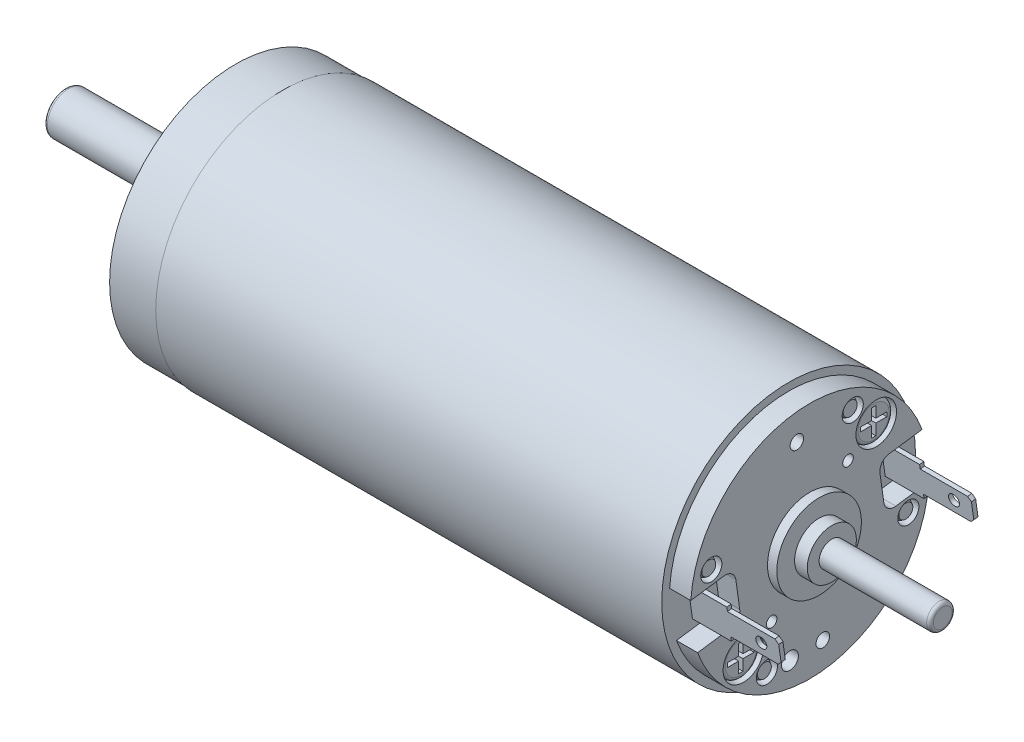
SolidWorks part; units mm, degrees
ref_plane "Front Plane" through (0, 0, 0) normal (0, 0, 1) x (1, 0, 0)
ref_plane "Top Plane" through (0, 0, 0) normal (0, 1, 0) x (1, 0, 0)
ref_plane "Right Plane" through (0, 0, 0) normal (1, 0, 0) x (0, 0, -1)
sketch "Sketch1" plane through (0, 0, 0) normal (0, 0, 1) x (1, 0, 0)
  line L0 (5.7, 15) -> (5.7, 0)
  line L1 (5.7, 0) -> (65.5, 0)
  line L2 (65.5, 0) -> (65.5, 15)
  line L3 (65.5, 15) -> (5.7, 15)
  line L4 (5.7, 0) -> (65.5, 0) construction
revolve "Revolve1" add sketch "Sketch1" angle 360 about L4
sketch "Sketch2" plane through (65.5, 0, 0) normal (1, 0, 0) x (0, 0, -1)
  line L0 (11.9001, -0.2462) -> (11.4049, -0.3158)
  line L1 (11.4049, -0.3158) -> (10.8761, 3.4472)
  line L2 (10.8761, 3.4472) -> (11.3712, 3.5168)
  line L3 (11.3712, 3.5168) -> (11.9001, -0.2462)
extrude "Boss-Extrude1" add sketch "Sketch2" along normal blind 10.6
sketch "Sketch3" plane through (0, 1.5657, -11.1405) normal (0, -0.1392, 0.9903) x (1, 0, 0)
  line L0 (70.1, 1.4) -> (76.1, 1.4)
  line L1 (76.1, 1.4) -> (76.1, 1.9)
  line L2 (76.1, 1.9) -> (70.1, 1.9)
  line L3 (70.1, 1.9) -> (70.1, 1.4)
extrude "Cut-Extrude1" cut sketch "Sketch3" against normal through all
sketch "Sketch4" plane through (0, 1.5657, -11.1405) normal (0, -0.1392, 0.9903) x (1, 0, 0)
  line L0 (70.1, -1.4) -> (70.1, -1.9)
  line L1 (70.1, -1.9) -> (76.1, -1.9)
  line L2 (76.1, -1.9) -> (76.1, -1.4)
  line L3 (76.1, -1.4) -> (70.1, -1.4)
extrude "Cut-Extrude2" cut sketch "Sketch4" against normal through all
sketch "Sketch5" plane through (65.5, 0, 0) normal (1, 0, 0) x (0, 0, -1)
  line L0 (-11.9001, 0.2462) -> (-11.4049, 0.3158)
  line L1 (-11.4049, 0.3158) -> (-10.8761, -3.4472)
  line L2 (-10.8761, -3.4472) -> (-11.3712, -3.5168)
  line L3 (-11.3712, -3.5168) -> (-11.9001, 0.2462)
extrude "Boss-Extrude2" add sketch "Sketch5" along normal blind 10.6
sketch "Sketch6" plane through (0, -1.5657, 11.1405) normal (0, 0.1392, -0.9903) x (-1, 0, 0)
  line L0 (-76.1, -1.9) -> (-70.1, -1.9)
  line L1 (-70.1, -1.9) -> (-70.1, -1.4)
  line L2 (-70.1, -1.4) -> (-76.1, -1.4)
  line L3 (-76.1, -1.4) -> (-76.1, -1.9)
extrude "Cut-Extrude3" cut sketch "Sketch6" against normal through all
sketch "Sketch7" plane through (0, -1.5657, 11.1405) normal (0, 0.1392, -0.9903) x (-1, 0, 0)
  line L0 (-76.1, 1.9) -> (-76.1, 1.4)
  line L1 (-76.1, 1.4) -> (-70.1, 1.4)
  line L2 (-70.1, 1.4) -> (-70.1, 1.9)
  line L3 (-70.1, 1.9) -> (-76.1, 1.9)
extrude "Cut-Extrude4" cut sketch "Sketch7" against normal through all
sketch "Sketch8" plane through (5.7, 0, 0) normal (-1, 0, 0) x (0, 0, 1)
  circle A0 centre (0, 0) radius 14.9
extrude "Boss-Extrude3" add sketch "Sketch8" along normal blind 5.55
sketch "Sketch9" plane through (0.15, 0, 0) normal (-1, 0, 0) x (0, 0, 1)
  circle A0 centre (0, 0) radius 13.5
extrude "Boss-Extrude4" add sketch "Sketch9" along normal blind 0.15
sketch "Sketch10" plane through (0, 0, 0) normal (-1, 0, 0) x (0, 0, 1)
  circle A0 centre (0, 0) radius 8
extrude "Boss-Extrude5" add sketch "Sketch10" along normal blind 1.1
sketch "Sketch11" plane through (-1.1, 0, 0) normal (-1, 0, 0) x (0, 0, 1)
  circle A0 centre (0, 0) radius 4.5
extrude "Boss-Extrude6" add sketch "Sketch11" along normal blind 2.15
sketch "Sketch12" plane through (-3.25, 0, 0) normal (-1, 0, 0) x (0, 0, 1)
  circle A0 centre (0, 0) radius 2.5
  dimension "D1" = 5
extrude "Boss-Extrude7" add sketch "Sketch12" along normal blind 16.75
sketch "Sketch13" plane through (65.5, 0, 0) normal (1, 0, 0) x (0, 0, -1)
  line L0 (-8.9199, 1.6749) -> (-14.0679, 0.9514)
  line L1 (13.2607, 4.7922) -> (8.1127, 4.0687)
  line L2 (8.1127, 4.0687) -> (8.9199, -1.6749)
  line L3 (8.9199, -1.6749) -> (14.0679, -0.9514)
  line L4 (-13.2607, -4.7922) -> (-8.1127, -4.0687)
  line L5 (-8.1127, -4.0687) -> (-8.9199, 1.6749)
  arc A0 (-14.0679, 0.9514) -> (13.2607, 4.7922) centre (0, 0) cw
  arc A1 (14.0679, -0.9514) -> (-13.2607, -4.7922) centre (0, 0) cw
extrude "Boss-Extrude8" add sketch "Sketch13" along normal blind 2.5
sketch "Sketch14" plane through (68, 0, 0) normal (1, 0, 0) x (0, 0, -1)
  circle A0 centre (0, 0) radius 5
extrude "Boss-Extrude9" add sketch "Sketch14" along normal blind 1.1
sketch "Sketch15" plane through (69.1, 0, 0) normal (1, 0, 0) x (0, 0, -1)
  circle A0 centre (0, 0) radius 2.9
extrude "Boss-Extrude10" add sketch "Sketch15" along normal blind 1.5
sketch "Sketch16" plane through (70.6, 0, 0) normal (1, 0, 0) x (0, 0, -1)
  circle A0 centre (0, 0) radius 1.5
extrude "Boss-Extrude11" add sketch "Sketch16" along normal blind 13.1
hole_wizard "Ø2.5 (2.5) Diameter Hole1" positions "Sketch18" profile "Sketch17" hole size "Ø2.5" standard "Ansi Metric"
sketch "Sketch18" plane through (68, 0, 0) normal (1, 0, 0) x (0, 0, -1)
  point P0 (11.6435, -2.9031)
sketch "Sketch17" plane through (68, -2.9031, -11.6435) normal (0, 1, 0) x (0, 0, -1)
  line L0 (0, 0) -> (0, 1.3)
  line L1 (0, 1.3) -> (1.25, 1.3)
  line L2 (1.25, 1.3) -> (1.25, 0)
  line L5 (1.25, 0) -> (0, 0)
  line L10 (0, 1.3) -> (-1.25, 1.3) construction
  line L11 (0, -6.35) -> (0, 107.95) construction
  dimension "Hole Dia." = 2.5
  dimension "Hole Depth" = 1.3
  dimension "Drill Angle" = 180
sketch "Sketch19" plane through (66.7, 0, 0) normal (1, 0, 0) x (0, 0, -1)
  circle A0 centre (11.6435, -2.9031) radius 1
extrude "Boss-Extrude12" add sketch "Sketch19" along normal blind 1
hole_wizard "Ø2.5 (2.5) Diameter Hole2" positions "Sketch21" profile "Sketch20" hole size "Ø2.5" standard "Ansi Metric"
sketch "Sketch21" plane through (68, 0, 0) normal (1, 0, 0) x (0, 0, -1)
  point P0 (5.0714, 10.8757)
sketch "Sketch20" plane through (68, 10.8757, -5.0714) normal (0, 1, 0) x (0, 0, -1)
  line L0 (0, 0) -> (0, 1.3)
  line L1 (0, 1.3) -> (1.25, 1.3)
  line L2 (1.25, 1.3) -> (1.25, 0)
  line L5 (1.25, 0) -> (0, 0)
  line L10 (0, 1.3) -> (-1.25, 1.3) construction
  line L11 (0, -6.35) -> (0, 107.95) construction
  dimension "Hole Dia." = 2.5
  dimension "Hole Depth" = 1.3
  dimension "Drill Angle" = 180
sketch "Sketch22" plane through (66.7, 0, 0) normal (1, 0, 0) x (0, 0, -1)
  circle A0 centre (5.0714, 10.8757) radius 1
extrude "Boss-Extrude13" add sketch "Sketch22" along normal blind 1
hole_wizard "Ø2.5 (2.5) Diameter Hole3" positions "Sketch24" profile "Sketch23" hole size "Ø2.5" standard "Ansi Metric"
sketch "Sketch24" plane through (68, 0, 0) normal (1, 0, 0) x (0, 0, -1)
  point P0 (-11.6435, 2.9031)
sketch "Sketch23" plane through (68, 2.9031, 11.6435) normal (0, 1, 0) x (0, 0, -1)
  line L0 (0, 0) -> (0, 1.3)
  line L1 (0, 1.3) -> (1.25, 1.3)
  line L2 (1.25, 1.3) -> (1.25, 0)
  line L5 (1.25, 0) -> (0, 0)
  line L10 (0, 1.3) -> (-1.25, 1.3) construction
  line L11 (0, -6.35) -> (0, 107.95) construction
  dimension "Hole Dia." = 2.5
  dimension "Hole Depth" = 1.3
  dimension "Drill Angle" = 180
sketch "Sketch25" plane through (66.7, 0, 0) normal (1, 0, 0) x (0, 0, -1)
  circle A0 centre (-11.6435, 2.9031) radius 1
extrude "Boss-Extrude14" add sketch "Sketch25" along normal blind 1
hole_wizard "Ø2.5 (2.5) Diameter Hole4" positions "Sketch27" profile "Sketch26" hole size "Ø2.5" standard "Ansi Metric"
sketch "Sketch27" plane through (68, 0, 0) normal (1, 0, 0) x (0, 0, -1)
  point P0 (-5.0714, -10.8757)
sketch "Sketch26" plane through (68, -10.8757, 5.0714) normal (0, 1, 0) x (0, 0, -1)
  line L0 (0, 0) -> (0, 1.3)
  line L1 (0, 1.3) -> (1.25, 1.3)
  line L2 (1.25, 1.3) -> (1.25, 0)
  line L5 (1.25, 0) -> (0, 0)
  line L10 (0, 1.3) -> (-1.25, 1.3) construction
  line L11 (0, -6.35) -> (0, 107.95) construction
  dimension "Hole Dia." = 2.5
  dimension "Hole Depth" = 1.3
  dimension "Drill Angle" = 180
sketch "Sketch28" plane through (66.7, 0, 0) normal (1, 0, 0) x (0, 0, -1)
  circle A0 centre (-5.0714, -10.8757) radius 1
extrude "Boss-Extrude15" add sketch "Sketch28" along normal blind 1
hole_wizard "Ø4.8 (4.8) Diameter Hole1" positions "Sketch30" profile "Sketch29" hole size "Ø4.8" standard "Ansi Metric"
sketch "Sketch30" plane through (68, 0, 0) normal (1, 0, 0) x (0, 0, -1)
  point P0 (7.8496, 8.1285)
sketch "Sketch29" plane through (68, 8.1285, -7.8496) normal (0, 1, 0) x (0, 0, -1)
  line L0 (0, 0) -> (0, 2.1)
  line L1 (0, 2.1) -> (2.4, 2.1)
  line L2 (2.4, 2.1) -> (2.4, 0)
  line L5 (2.4, 0) -> (0, 0)
  line L10 (0, 2.1) -> (-2.4, 2.1) construction
  line L11 (0, -6.35) -> (0, 107.95) construction
  dimension "Hole Dia." = 4.8
  dimension "Hole Depth" = 2.1
  dimension "Drill Angle" = 180
sketch "Sketch31" plane through (65.9, 0, 0) normal (1, 0, 0) x (0, 0, -1)
  circle A0 centre (7.8496, 8.1285) radius 2.25
extrude "Boss-Extrude16" add sketch "Sketch31" along normal blind 1.8
sketch "Sketch32" plane through (67.7, 0, 0) normal (1, 0, 0) x (0, 0, -1)
  line L0 (7.5996, 8.3785) -> (6.2996, 8.3785)
  line L1 (6.2996, 8.3785) -> (6.2996, 7.8785)
  line L2 (6.2996, 7.8785) -> (7.5996, 7.8785)
  line L3 (7.5996, 7.8785) -> (7.5996, 6.5785)
  line L4 (7.5996, 6.5785) -> (8.0996, 6.5785)
  line L5 (8.0996, 6.5785) -> (8.0996, 7.8785)
  line L6 (8.0996, 7.8785) -> (9.3996, 7.8785)
  line L7 (9.3996, 7.8785) -> (9.3996, 8.3785)
  line L8 (9.3996, 8.3785) -> (8.0996, 8.3785)
  line L9 (8.0996, 8.3785) -> (8.0996, 9.6785)
  line L10 (8.0996, 9.6785) -> (7.5996, 9.6785)
  line L11 (7.5996, 9.6785) -> (7.5996, 8.3785)
extrude "Cut-Extrude5" cut sketch "Sketch32" against normal blind 1.2
hole_wizard "Ø4.8 (4.8) Diameter Hole2" positions "Sketch34" profile "Sketch33" hole size "Ø4.8" standard "Ansi Metric"
sketch "Sketch34" plane through (68, 0, 0) normal (1, 0, 0) x (0, 0, -1)
  point P0 (-7.8496, -8.1285)
sketch "Sketch33" plane through (68, -8.1285, 7.8496) normal (0, 1, 0) x (0, 0, -1)
  line L0 (0, 0) -> (0, 2.1)
  line L1 (0, 2.1) -> (2.4, 2.1)
  line L2 (2.4, 2.1) -> (2.4, 0)
  line L5 (2.4, 0) -> (0, 0)
  line L10 (0, 2.1) -> (-2.4, 2.1) construction
  line L11 (0, -6.35) -> (0, 107.95) construction
  dimension "Hole Dia." = 4.8
  dimension "Hole Depth" = 2.1
  dimension "Drill Angle" = 180
sketch "Sketch35" plane through (65.9, 0, 0) normal (1, 0, 0) x (0, 0, -1)
  circle A0 centre (-7.8496, -8.1285) radius 2.25
extrude "Boss-Extrude17" add sketch "Sketch35" along normal blind 1.8
sketch "Sketch36" plane through (67.7, 0, 0) normal (1, 0, 0) x (0, 0, -1)
  line L0 (-8.0996, -7.8785) -> (-9.3996, -7.8785)
  line L1 (-9.3996, -7.8785) -> (-9.3996, -8.3785)
  line L2 (-9.3996, -8.3785) -> (-8.0996, -8.3785)
  line L3 (-8.0996, -8.3785) -> (-8.0996, -9.6785)
  line L4 (-8.0996, -9.6785) -> (-7.5996, -9.6785)
  line L5 (-7.5996, -9.6785) -> (-7.5996, -8.3785)
  line L6 (-7.5996, -8.3785) -> (-6.2996, -8.3785)
  line L7 (-6.2996, -8.3785) -> (-6.2996, -7.8785)
  line L8 (-6.2996, -7.8785) -> (-7.5996, -7.8785)
  line L9 (-7.5996, -7.8785) -> (-7.5996, -6.5785)
  line L10 (-7.5996, -6.5785) -> (-8.0996, -6.5785)
  line L11 (-8.0996, -6.5785) -> (-8.0996, -7.8785)
extrude "Cut-Extrude6" cut sketch "Sketch36" against normal blind 1.2
hole_wizard "Ø1.3 (1.3) Diameter Hole1" positions "Sketch38" profile "Sketch37" hole size "Ø1.3" standard "Ansi Metric"
sketch "Sketch38" plane through (0, -1.5657, 11.1405) normal (0, 0.1392, -0.9903) x (-1, 0, 0)
  point P0 (-73.9, 0)
sketch "Sketch37" plane through (73.9, -1.5657, 11.1405) normal (1, 0, 0) x (0, 0.9903, 0.1392)
  line L0 (0, 0) -> (0, 5.6916)
  line L1 (0, 5.6916) -> (0.65, 5.6916)
  line L2 (0.65, 5.6916) -> (0.65, 0)
  line L5 (0.65, 0) -> (0, 0)
  line L11 (0, -6.35) -> (0, 107.95) construction
  dimension "Thru Hole Dia." = 1.3
  dimension "Thru Hole Depth" = 5.6916
hole_wizard "Ø1.3 (1.3) Diameter Hole2" positions "Sketch40" profile "Sketch39" hole size "Ø1.3" standard "Ansi Metric"
sketch "Sketch40" plane through (0, 1.5657, -11.1405) normal (0, -0.1392, 0.9903) x (1, 0, 0)
  point P0 (73.9, 0)
sketch "Sketch39" plane through (73.9, 1.5657, -11.1405) normal (1, 0, 0) x (0, -0.9903, -0.1392)
  line L0 (0, 0) -> (0, 5.6916)
  line L1 (0, 5.6916) -> (0.65, 5.6916)
  line L2 (0.65, 5.6916) -> (0.65, 0)
  line L5 (0.65, 0) -> (0, 0)
  line L11 (0, -6.35) -> (0, 107.95) construction
  dimension "Thru Hole Dia." = 1.3
  dimension "Thru Hole Depth" = 5.6916
hole_wizard "Ø2.0 (2) Diameter Hole1" positions "Sketch42" profile "Sketch41" hole size "Ø2.0" standard "Ansi Metric"
sketch "Sketch42" plane through (68, 0, 0) normal (1, 0, 0) x (0, 0, -1)
  point P0 (-2.3494, -11.0531)
sketch "Sketch41" plane through (68, -11.0531, 2.3494) normal (0, 1, 0) x (0, 0, -1)
  line L0 (0, 0) -> (0, 3.3)
  line L1 (0, 3.3) -> (1, 3.3)
  line L2 (1, 3.3) -> (1, 0)
  line L5 (1, 0) -> (0, 0)
  line L10 (0, 3.3) -> (-1, 3.3) construction
  line L11 (0, -6.35) -> (0, 107.95) construction
  dimension "Hole Dia." = 2
  dimension "Hole Depth" = 3.3
  dimension "Drill Angle" = 180
hole_wizard "Ø1.6 (1.6) Diameter Hole1" positions "Sketch44" profile "Sketch43" hole size "Ø1.6" standard "Ansi Metric"
sketch "Sketch44" plane through (68, 0, 0) normal (1, 0, 0) x (0, 0, -1)
  point P0 (1.5309, -10.8929)
  point P1 (-1.5309, 10.8929)
sketch "Sketch43" plane through (68, -10.8929, -1.5309) normal (0, 1, 0) x (0, 0, -1)
  line L0 (0, 0) -> (0, 5.2619)
  line L1 (0, 5.2619) -> (0.8, 4.8)
  line L2 (0.8, 4.8) -> (0.8, 0)
  line L5 (0.8, 0) -> (0, 0)
  line L10 (0, 5.2619) -> (-0.8, 4.8) construction
  line L11 (0, -6.35) -> (0, 107.95) construction
  dimension "Hole Dia." = 1.6
  dimension "Hole Depth" = 4.8
  dimension "Drill Angle" = 120
hole_wizard "Ø1.25 (1.25) Diameter Hole1" positions "Sketch46" profile "Sketch45" hole size "Ø1.25" standard "Ansi Metric"
sketch "Sketch46" plane through (68, 0, 0) normal (1, 0, 0) x (0, 0, -1)
  point P0 (4.5136, 5.9898)
  point P1 (-4.5136, -5.9898)
sketch "Sketch45" plane through (68, 5.9898, -4.5136) normal (0, 1, 0) x (0, 0, -1)
  line L0 (0, 0) -> (0, 4.1108)
  line L1 (0, 4.1108) -> (0.625, 3.75)
  line L2 (0.625, 3.75) -> (0.625, 0)
  line L5 (0.625, 0) -> (0, 0)
  line L10 (0, 4.1108) -> (-0.625, 3.75) construction
  line L11 (0, -6.35) -> (0, 107.95) construction
  dimension "Hole Dia." = 1.25
  dimension "Hole Depth" = 3.75
  dimension "Drill Angle" = 120
hole_wizard "Ø1.5 (1.5) Diameter Hole1" positions "Sketch48" profile "Sketch47" hole size "Ø1.5" standard "Ansi Metric"
sketch "Sketch48" plane through (0, 0, 0) normal (-1, 0, 0) x (0, 0, 1)
  point P0 (-6, 10.3923)
sketch "Sketch47" plane through (0, 10.3923, -6) normal (0, 1, 0) x (0, 0, 1)
  line L0 (0, 0) -> (0, 1.933)
  line L1 (0, 1.933) -> (0.75, 1.5)
  line L2 (0.75, 1.5) -> (0.75, 0)
  line L5 (0.75, 0) -> (0, 0)
  line L10 (0, 1.933) -> (-0.75, 1.5) construction
  line L11 (0, -6.35) -> (0, 107.95) construction
  dimension "Hole Dia." = 1.5
  dimension "Hole Depth" = 1.5
  dimension "Drill Angle" = 120
hole_wizard "Ø2.5 (2.5) Diameter Hole5" positions "Sketch50" profile "Sketch49" hole size "Ø2.5" standard "Ansi Metric"
sketch "Sketch50" plane through (0, 0, 0) normal (-1, 0, 0) x (0, 0, 1)
  point P0 (0, 11)
  point P1 (9.5263, 5.5)
  point P2 (9.5263, -5.5)
  point P3 (0, -11)
  point P4 (-9.5263, -5.5)
  point P5 (-9.5263, 5.5)
sketch "Sketch49" plane through (0, 11, 0) normal (0, 1, 0) x (0, 0, 1)
  line L0 (0, 0) -> (0, 6.8217)
  line L1 (0, 6.8217) -> (1.25, 6.1)
  line L2 (1.25, 6.1) -> (1.25, 0)
  line L5 (1.25, 0) -> (0, 0)
  line L10 (0, 6.8217) -> (-1.25, 6.1) construction
  line L11 (0, -6.35) -> (0, 107.95) construction
  dimension "Hole Dia." = 2.5
  dimension "Hole Depth" = 6.1
  dimension "Drill Angle" = 120
chamfer "Chamfer1" distance 0.4 angle 45 4 edges at (76.1, 0.2141, -11.5829) (76.1, -0.2141, 11.5829) (76.1, 2.9869, -11.1932) (76.1, -2.9869, 11.1932)
chamfer "Chamfer2" distance 0.1732 angle 60 3 edges at (67.7, 10.8757, -6.0714) (67.7, 2.9031, 10.6435) (67.7, -2.9031, -12.6435)
chamfer "Chamfer3" distance 0.3 angle 30 1 edges at (67.7, -10.8757, 4.0714)
fillet "Fillet1" radius 0.4 4 edges at (-20, 0, 2.5) (67.7, -8.1285, 5.5996) (83.7, 0, -1.5) (67.7, 8.1285, -10.0996)
fillet "Fillet2" radius 1.25 4 edges at (66.75, 4.0687, -8.1127) (66.75, 1.6749, 8.9199) (66.75, -1.6749, -8.9199) (66.75, -4.0687, 8.1127)
